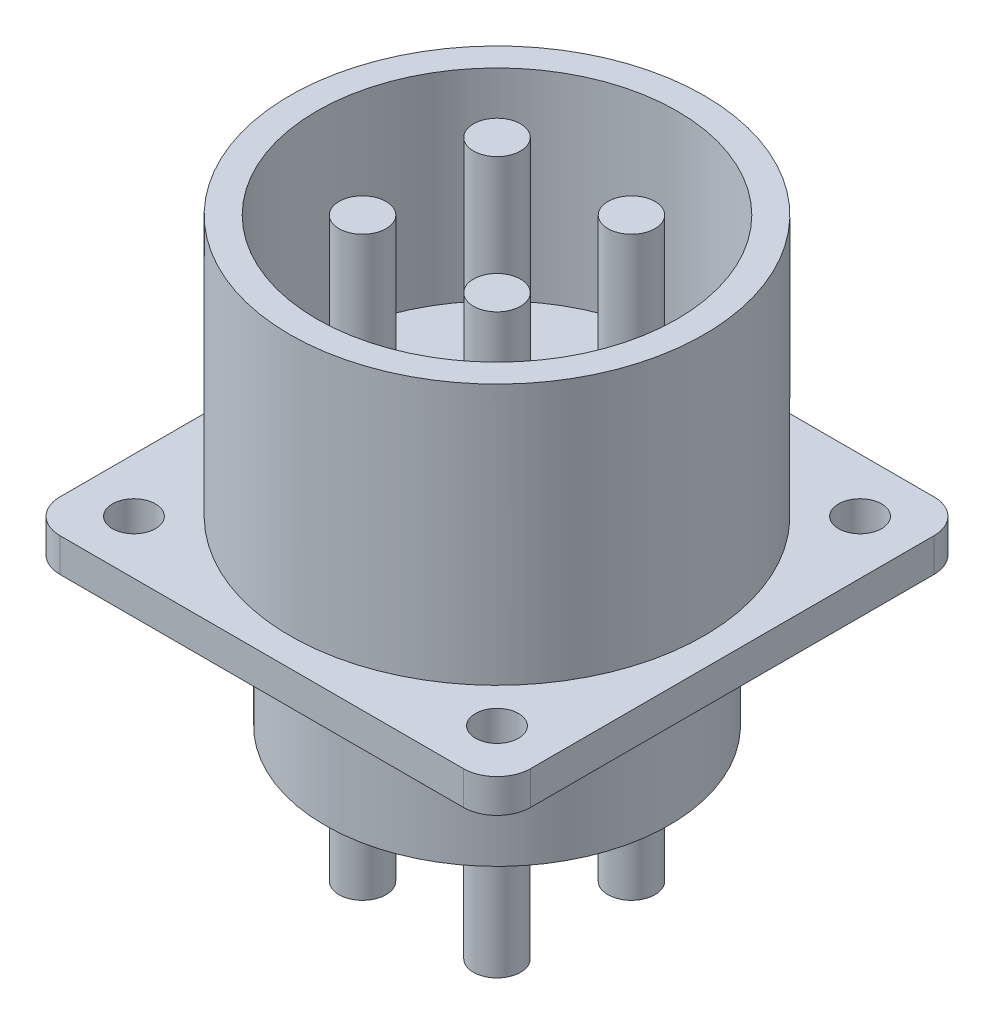
SolidWorks part; units mm, degrees
ref_plane "Front Plane" through (0, 0, 0) normal (0, 0, 1) x (1, 0, 0)
ref_plane "Top Plane" through (0, 0, 0) normal (0, 1, 0) x (1, 0, 0)
ref_plane "Right Plane" through (0, 0, 0) normal (1, 0, 0) x (0, 0, -1)
sketch "Sketch1" plane through (0, 0, 0) normal (0, 1, 0) x (1, 0, 0)
  line L1 (-17.5, -17.5) -> (17.5, -17.5)
  line L2 (-17.5, -17.5) -> (-17.5, 17.5)
  line L3 (-17.5, 17.5) -> (17.5, 17.5)
  line L4 (17.5, -17.5) -> (17.5, 17.5)
  line L5 (-17.5, -17.5) -> (17.5, 17.5) construction
  line L6 (-17.5, 17.5) -> (17.5, -17.5) construction
  point P0 (0, 0)
  dimension "D1" = 35
  dimension "D2" = 35
extrude "Boss-Extrude1" add sketch "Sketch1" along normal blind 2.5
fillet "Fillet1" radius 2.5 4 edges at (17.5, 1.25, -17.5) (-17.5, 1.25, -17.5) (-17.5, 1.25, 17.5) (17.5, 1.25, 17.5)
sketch "Sketch2" plane through (0, 2.5, 0) normal (0, 1, 0) x (1, 0, 0)
  circle A0 centre (0, 0) radius 15.4
  dimension "D1" = 30.8
extrude "Boss-Extrude2" add sketch "Sketch2" along normal blind 19.4
sketch "Sketch3" plane through (0, 0, 0) normal (0, -1, 0) x (1, 0, 0)
  circle A0 centre (0, 0) radius 12.8
  dimension "D1" = 25.6
extrude "Boss-Extrude3" add sketch "Sketch3" along normal blind 11
sketch "Sketch4" plane through (0, 21.9, 0) normal (0, 1, 0) x (1, 0, 0)
  circle A2 centre (0, 0) radius 13.4
  circle A3 centre (0, 0) radius 13.4
  dimension "D1" = 2
extrude "Cut-Extrude1" cut sketch "Sketch4" against normal blind 15
sketch "Sketch5" plane through (0, 6.9, 0) normal (0, 1, 0) x (1, 0, 0)
  line L1 (-5, -5) -> (5, -5) construction
  line L2 (-5, -5) -> (-5, 5) construction
  line L3 (-5, 5) -> (5, 5) construction
  line L4 (5, -5) -> (5, 5) construction
  line L5 (-5, -5) -> (5, 5) construction
  line L6 (-5, 5) -> (5, -5) construction
  circle A0 centre (-5, 5) radius 1.75
  circle A1 centre (-5, -5) radius 1.75
  circle A2 centre (5, -5) radius 1.75
  circle A3 centre (5, 5) radius 1.75
  point P0 (0, 0)
  dimension "D1" = 3.5
  dimension "D2" = 10
  dimension "D3" = 10
extrude "Boss-Extrude4" add sketch "Sketch5" along normal blind 15
sketch "Sketch6" plane through (0, -11, 0) normal (0, -1, 0) x (1, 0, 0)
  circle A1 centre (5, -5) radius 1.75
  circle A2 centre (5, -5) radius 1.75
  circle A3 centre (5, 5) radius 1.75
  circle A4 centre (5, 5) radius 1.75
  circle A5 centre (-5, 5) radius 1.75
  circle A6 centre (-5, 5) radius 1.75
  circle A7 centre (-5, -5) radius 1.75
  circle A8 centre (-5, -5) radius 1.75
  dimension "D1" = 0
  dimension "D2" = 0
  dimension "D3" = 0
  dimension "D4" = 0
extrude "Boss-Extrude5" add sketch "Sketch6" along normal blind 10
sketch "Sketch7" plane through (0, 2.5, 0) normal (0, 1, 0) x (1, 0, 0)
  line L1 (-13.5, -13.5) -> (13.5, -13.5) construction
  line L2 (-13.5, -13.5) -> (-13.5, 13.5) construction
  line L3 (-13.5, 13.5) -> (13.5, 13.5) construction
  line L4 (13.5, -13.5) -> (13.5, 13.5) construction
  line L5 (-13.5, -13.5) -> (13.5, 13.5) construction
  line L6 (-13.5, 13.5) -> (13.5, -13.5) construction
  circle A0 centre (-13.5, 13.5) radius 1.6
  circle A1 centre (-13.5, -13.5) radius 1.6
  circle A2 centre (13.5, -13.5) radius 1.6
  circle A3 centre (13.5, 13.5) radius 1.6
  point P0 (0, 0)
  dimension "D3" = 3.2
  dimension "D1" = 27
  dimension "D2" = 27
extrude "Cut-Extrude2" cut sketch "Sketch7" against normal through all
